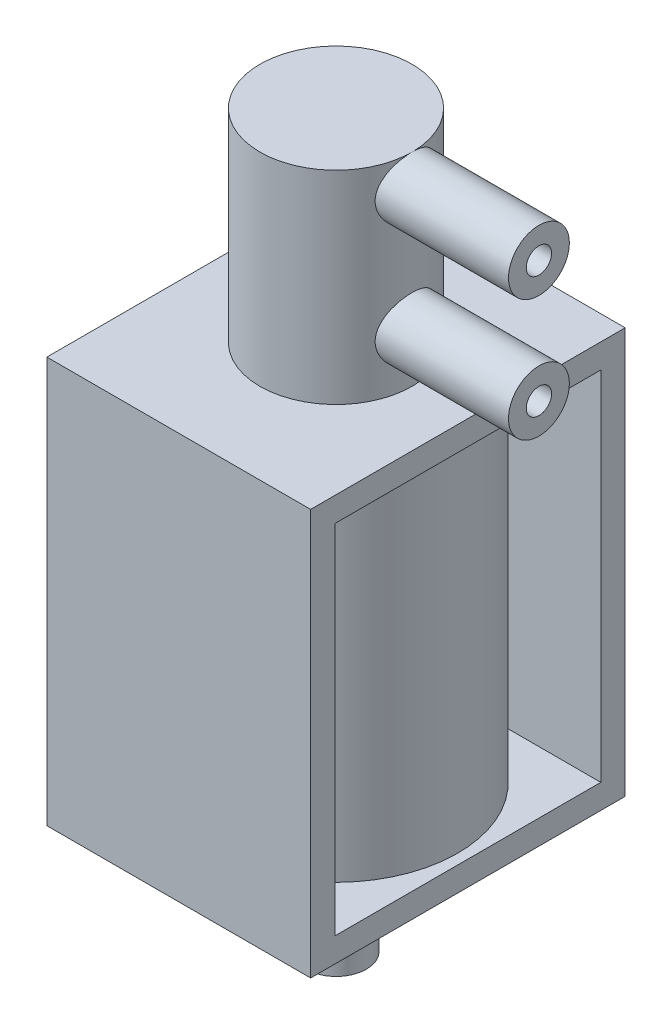
SolidWorks part; units mm, degrees
ref_plane "Спереди" through (0, 0, 0) normal (0, 0, 1) x (1, 0, 0)
ref_plane "Сверху" through (0, 0, 0) normal (0, 1, 0) x (1, 0, 0)
ref_plane "Справа" through (0, 0, 0) normal (1, 0, 0) x (0, 0, -1)
sketch "Эскиз1" plane through (0, 0, 0) normal (0, 1, 0) x (1, 0, 0)
  line L1 (-6.5, 7.75) -> (6.5, 7.75)
  line L2 (-6.5, 7.75) -> (-6.5, -7.75)
  line L3 (-6.5, -7.75) -> (6.5, -7.75)
  line L4 (6.5, 7.75) -> (6.5, -7.75)
  line L5 (-6.5, 7.75) -> (6.5, -7.75) construction
  line L6 (-6.5, -7.75) -> (6.5, 7.75) construction
  point P0 (0, 0)
  dimension "D1" = 13
  dimension "D2" = 15.5
extrude "База" add sketch "Эскиз1" along normal blind 20
sketch "Эскиз2" plane through (0, 0, 0) normal (0, -1, 0) x (1, 0, 0)
  circle A0 centre (0, 0) radius 1.5
  circle A1 centre (0, 0) radius 0.625
  dimension "D1" = 3
  dimension "D2" = 1.25
extrude "ТрубкаНиз-3мм" add sketch "Эскиз2" along normal blind 6
sketch "Эскиз3" plane through (0, 20, 0) normal (0, 1, 0) x (1, 0, 0)
  circle A0 centre (0, 0) radius 3.75
  dimension "D1" = 7.5
extrude "ТрубкаВерх" add sketch "Эскиз3" along normal blind 10
sketch "Эскиз4" plane through (0, 0, 0) normal (1, 0, 0) x (0, 0, -1)
  line L0 (3.75, 30) -> (-3.75, 30) construction
  line L2 (-7.75, 20) -> (7.75, 20) construction
  circle A0 centre (0, 28.5) radius 1.5
  circle A1 centre (0, 22.5) radius 1.5
  circle A2 centre (0, 22.5) radius 0.625
  circle A3 centre (0, 28.5) radius 0.625
  dimension "D1" = 3
  dimension "D3" = 1.25
  dimension "D2" = 2.5
extrude "Отводы" add sketch "Эскиз4" along normal blind 10 separate body
sketch "Эскиз6" plane through (6.5, 0, 0) normal (1, 0, 0) x (0, 0, -1)
  line L0 (-7.75, 20) -> (-7.75, 0) construction
  line L1 (-6.55, 18.8) -> (6.55, 18.8)
  line L2 (-6.55, 18.8) -> (-6.55, 1.2)
  line L3 (-6.55, 1.2) -> (6.55, 1.2)
  line L4 (6.55, 18.8) -> (6.55, 1.2)
  line L5 (-6.55, 1.2) -> (-7.75, 1.2) construction
  line L6 (6.55, 1.2) -> (7.75, 1.2) construction
  line L7 (7.75, 20) -> (7.75, 0) construction
  line L8 (6.55, 1.2) -> (6.55, 0) construction
  line L9 (-7.75, 0) -> (7.75, 0) construction
  line L10 (6.55, 18.8) -> (6.55, 20) construction
  line L11 (-7.75, 20) -> (7.75, 20) construction
  point P4 (0, 1.2)
  point P8 (-7.75, 10)
  point P9 (-6.55, 10)
  dimension "D1" = 1.2
extrude "Вырез-Вытянуть1" cut sketch "Эскиз6" against normal through all
sketch "Эскиз7" plane through (0, 1.2, 0) normal (0, 1, 0) x (1, 0, 0)
  circle A0 centre (0, 0) radius 6
  dimension "D1" = 12
extrude "Бобышка-Вытянуть1" add sketch "Эскиз7" along normal up to next
